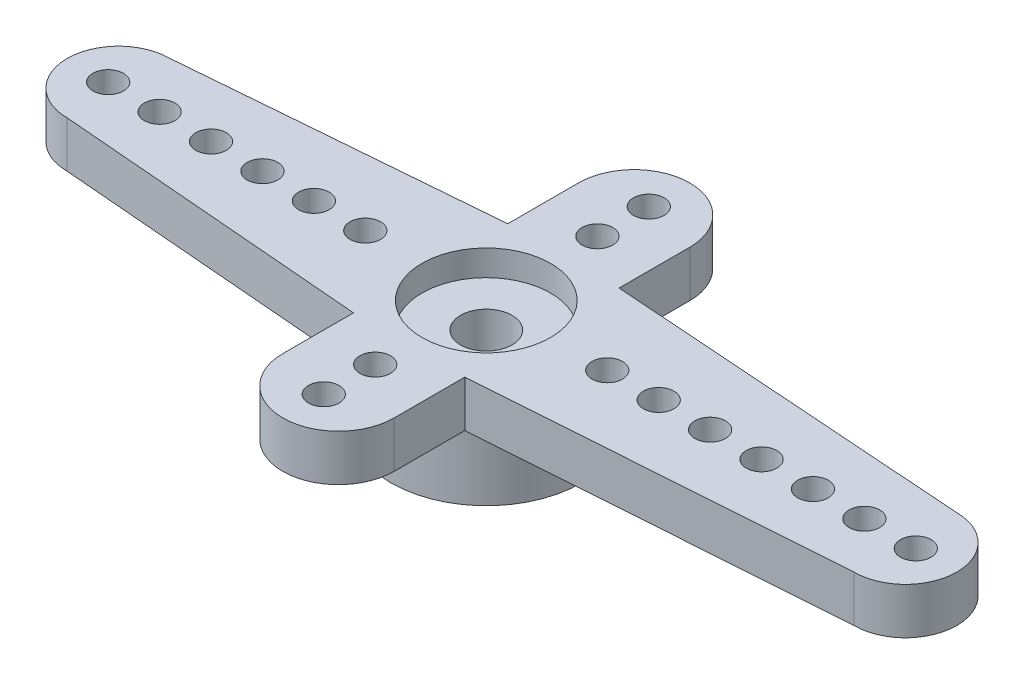
SolidWorks part; units mm, degrees
ref_plane "Alzado" through (0, 0, 0) normal (0, 0, 1) x (1, 0, 0)
ref_plane "Planta" through (0, 0, 0) normal (0, 1, 0) x (1, 0, 0)
ref_plane "Vista lateral" through (0, 0, 0) normal (1, 0, 0) x (0, 0, -1)
sketch "Croquis1" plane through (0, 0, 0) normal (0, 1, 0) x (1, 0, 0)
  circle A0 centre (0, 0) radius 3.7
  dimension "D1" = 7.4
extrude "Saliente-Extruir2" add sketch "Croquis1" along normal blind 4.3 contours A0
sketch "Croquis2" plane through (0, 0, 0) normal (0, -1, 0) x (1, 0, 0)
  circle A0 centre (0, 0) radius 2.5
  dimension "D1" = 5
extrude "Cortar-Extruir1" cut sketch "Croquis2" against normal blind 1.5
sketch "Croquis3" plane through (0, 4.3, 0) normal (0, 1, 0) x (1, 0, 0)
  circle A0 centre (0, 0) radius 2.5
  dimension "D1" = 5
extrude "Cortar-Extruir2" cut sketch "Croquis3" against normal blind 1
sketch "Croquis4" plane through (0, 3.3, 0) normal (0, 1, 0) x (1, 0, 0)
  circle A0 centre (0, 0) radius 1
  dimension "D1" = 2
extrude "Cortar-Extruir3" cut sketch "Croquis4" against normal blind 1.8
sketch "Croquis5" plane through (0, 4.3, 0) normal (0, 1, 0) x (1, 0, 0)
  line L0 (0, 0) -> (-2.1656, 0) construction
  line L1 (-2.1656, 3) -> (-3.1202, 0)
  line L2 (-3.1202, 0) -> (-2.1656, -3)
  line L3 (-2.1656, 0) -> (-2.5, 0) construction
  line L4 (-3.7, 0) -> (-16.3, 0) construction
  line L5 (-14.3, 0) -> (-14.3, 2) construction
  line L6 (-14.3, 0) -> (-14.3, -2) construction
  line L7 (-2.1656, 3) -> (-14.3, 2)
  line L8 (-2.1656, -3) -> (-14.3, -2)
  line L9 (0, 5.1944) -> (0, -4.3435) construction
  line L10 (3.1202, 0) -> (2.1656, -3)
  line L11 (2.1656, 3) -> (16.3, 2)
  line L12 (2.1656, -3) -> (16.3, -2)
  line L13 (2.1656, 3) -> (3.1202, 0)
  line L14 (3.7, 0) -> (18.3, 0) construction
  line L15 (16.3, 0) -> (16.3, 2) construction
  line L16 (16.3, 0) -> (16.3, -2) construction
  arc A0 (-14.3, 2) -> (-14.3, -2) centre (-14.3, 0) ccw
  arc A1 (16.3, 2) -> (16.3, -2) centre (16.3, 0) cw
  circle A3 centre (0, 0) radius 3.7 construction
  circle A4 centre (0, 0) radius 2.5 construction
  point P2 (-14.3, 0)
  point P30 (16.3, 0)
  dimension "D1" = 2.1656
  dimension "D2" = 12.6
  dimension "D3" = 2
  dimension "D4" = 2
  dimension "D5" = 2
  dimension "D6" = 14.6
  dimension "D7" = 2
extrude "Saliente-Extruir3" add sketch "Croquis5" against normal blind 1.8
sketch "Croquis6" plane through (0, 4.3, 0) normal (0, 1, 0) x (1, 0, 0)
  line L0 (0, 0) -> (-16.3, 0) construction
  line L1 (2, 0) -> (-14.3, 0) construction
  line L2 (4, 0) -> (-12.3, 0) construction
  line L3 (6, 0) -> (-10.3, 0) construction
  line L4 (8, 0) -> (-8.3, 0) construction
  line L5 (10, 0) -> (-6.3, 0) construction
  line L6 (0, 5.4913) -> (0, -4.5375) construction
  arc A0 (-14.3, 2) -> (-14.3, -2) centre (-14.3, 0) ccw construction
  circle A1 centre (-14.705, 0) radius 0.595
  circle A2 centre (-12.705, 0) radius 0.595
  circle A3 centre (-10.705, 0) radius 0.595
  circle A4 centre (-8.705, 0) radius 0.595
  circle A5 centre (-6.705, 0) radius 0.595
  circle A6 centre (-4.705, 0) radius 0.595
  circle A7 centre (14.705, 0) radius 0.595
  circle A8 centre (12.705, 0) radius 0.595
  circle A9 centre (10.705, 0) radius 0.595
  circle A10 centre (8.705, 0) radius 0.595
  circle A11 centre (6.705, 0) radius 0.595
  circle A12 centre (4.705, 0) radius 0.595
  circle A13 centre (16.705, 0) radius 0.595
  point P6 (-14.705, 0)
  dimension "D2" = 1.19
  dimension "D1" = 1.595
  dimension "D3" = 6
  dimension "D4" = 2
extrude "Cortar-Extruir4" cut sketch "Croquis6" against normal blind 1.8
sketch "Croquis7" plane through (0, 4.3, 0) normal (0, 1, 0) x (1, 0, 0)
  line L0 (-2.1656, 3) -> (2.1656, 3)
  line L1 (2.1656, 3) -> (2.1656, 5.75)
  line L2 (-2.1656, 3) -> (-2.1656, 5.75)
  line L3 (-16.3, 0) -> (18.3, 0) construction
  line L4 (0, 7.9156) -> (0, 6.3206) construction
  line L7 (0, 5.9156) -> (0, 4.3206) construction
  line L8 (2.1656, -3) -> (2.1656, -5.75)
  line L9 (-2.1656, -3) -> (-2.1656, -5.75)
  line L10 (-2.1656, -3) -> (2.1656, -3)
  line L11 (10, 7.9156) -> (10, 6.3206) construction
  line L12 (10, 5.9156) -> (10, 4.3206) construction
  arc A0 (2.1656, 5.75) -> (-2.1656, 5.75) centre (0, 5.75) ccw
  arc A1 (-14.3, 2) -> (-14.3, -2) centre (-14.3, 0) ccw construction
  arc A2 (16.3, -2) -> (16.3, 2) centre (16.3, 0) ccw construction
  circle A3 centre (0, 6.3206) radius 0.595
  circle A6 centre (0, 4.3206) radius 0.595
  circle A7 centre (0, -4.3206) radius 0.595
  circle A8 centre (0, -6.3206) radius 0.595
  arc A9 (2.1656, -5.75) -> (-2.1656, -5.75) centre (0, -5.75) cw
  circle A10 centre (10, 6.3206) radius 0.595 [skipped]
  circle A11 centre (10, 4.3206) radius 0.595 [skipped]
  dimension "D2" = 1.595
  dimension "D3" = 1.19
  dimension "D1" = 2.75
  dimension "D4" = 2
  dimension "D5" = 2
extrude "Saliente-Extruir4" add sketch "Croquis7" against normal blind 1.8
